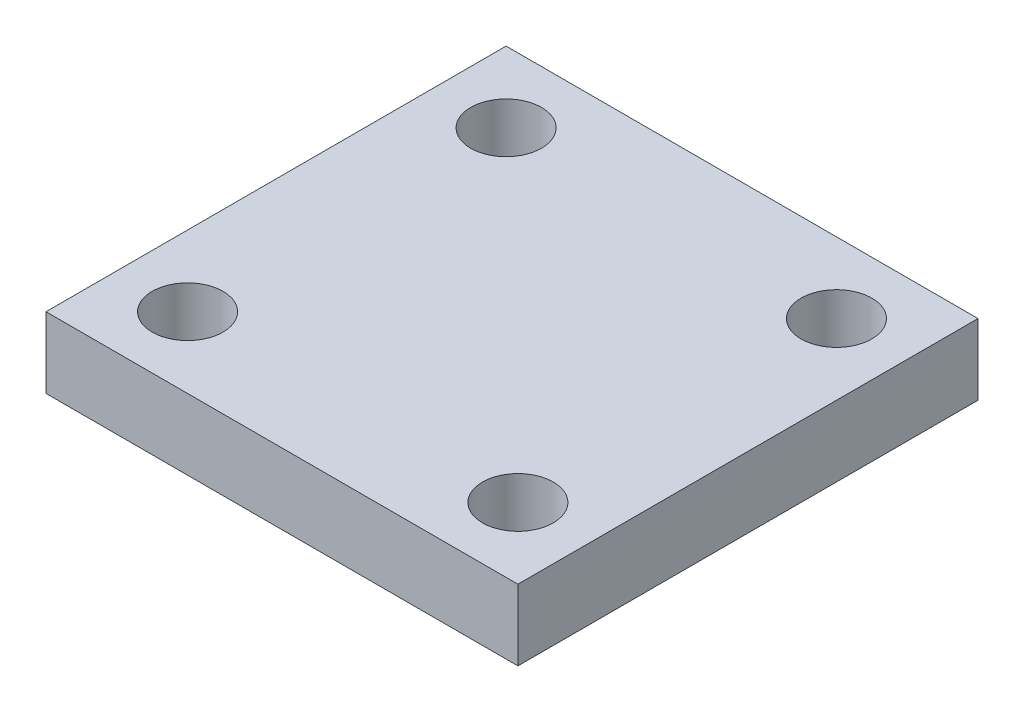
SolidWorks part; units mm, degrees
ref_plane "Спереди" through (0, 0, 0) normal (0, 0, 1) x (1, 0, 0)
ref_plane "Сверху" through (0, 0, 0) normal (0, 1, 0) x (1, 0, 0)
ref_plane "Справа" through (0, 0, 0) normal (1, 0, 0) x (0, 0, -1)
sketch "Sketch1" plane through (0, 0, 0) normal (0, 1, 0) x (1, 0, 0)
  line L1 (0, 0) -> (20, 0)
  line L2 (0, 0) -> (0, 19.5)
  line L3 (0, 19.5) -> (20, 19.5)
  line L4 (20, 0) -> (20, 19.5)
  circle A0 centre (3, 3) radius 1.5
  circle A1 centre (17, 3) radius 1.5
  circle A2 centre (17, 16.5) radius 1.5
  circle A3 centre (3, 16.5) radius 1.5
  dimension "D3" = 3
  dimension "D1" = 19.5
  dimension "D2" = 20
  dimension "D4" = 3
  dimension "D5" = 3
  dimension "D6" = 2
  dimension "D7" = 2
extrude "Boss-Extrude1" add sketch "Sketch1" along normal blind 3
